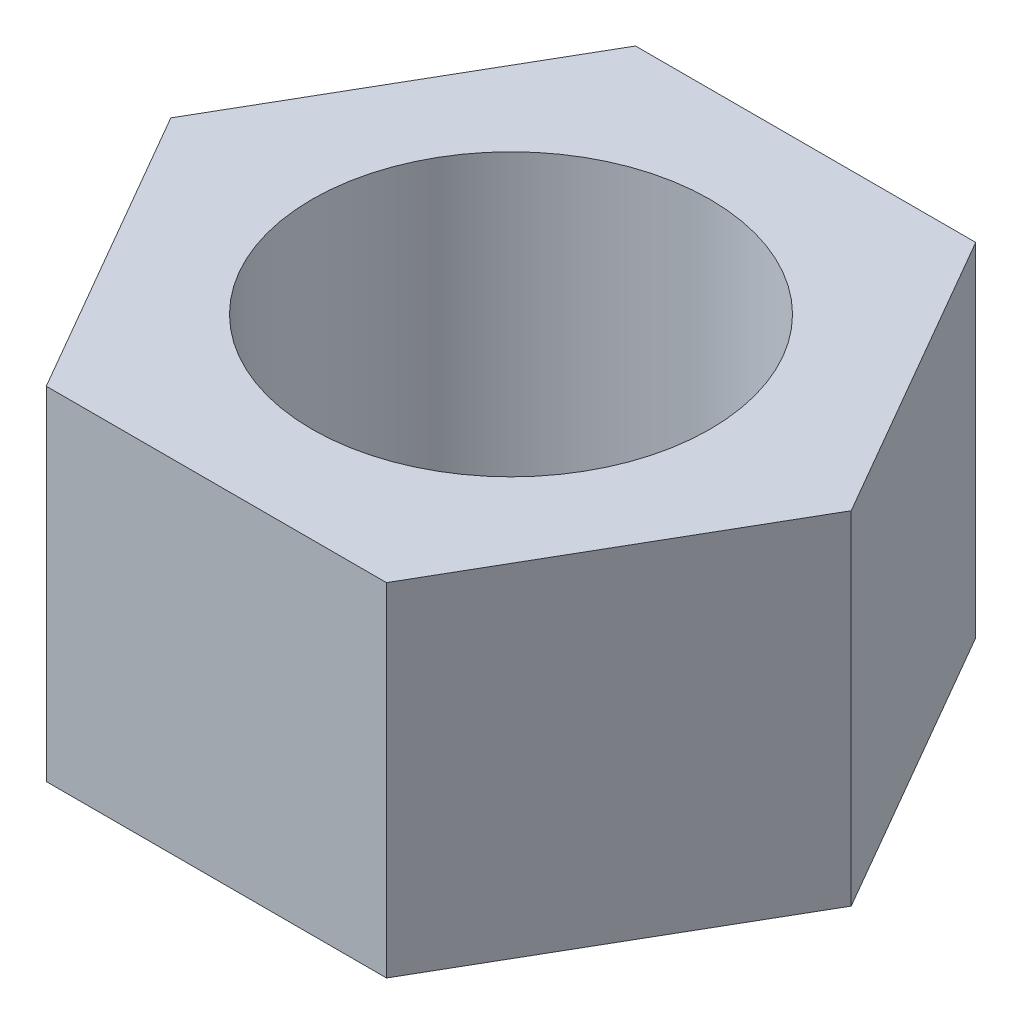
SolidWorks part; units mm, degrees
ref_plane "Front Plane" through (0, 0, 0) normal (0, 0, 1) x (1, 0, 0)
ref_plane "Top Plane" through (0, 0, 0) normal (0, 1, 0) x (1, 0, 0)
ref_plane "Right Plane" through (0, 0, 0) normal (1, 0, 0) x (0, 0, -1)
sketch "Sketch1" plane through (0, 0, 0) normal (0, 1, 0) x (1, 0, 0)
  line L1 (5.4259, -9.398) -> (10.8519, 0)
  line L2 (10.8519, 0) -> (5.4259, 9.398)
  line L3 (5.4259, 9.398) -> (-5.4259, 9.398)
  line L4 (-5.4259, 9.398) -> (-10.8519, 0)
  line L5 (-10.8519, 0) -> (-5.4259, -9.398)
  line L6 (-5.4259, -9.398) -> (5.4259, -9.398)
  circle A0 centre (0, 0) radius 9.398 construction
  dimension "D1" = 18.796
extrude "Boss-Extrude1" add sketch "Sketch1" along normal blind 10.922
sketch "Sketch2" plane through (0, 10.922, 0) normal (0, 1, 0) x (1, 0, 0)
  circle A0 centre (0, 0) radius 6.35
  dimension "D1" = 12.7
extrude "Cut-Extrude1" cut sketch "Sketch2" against normal through all
